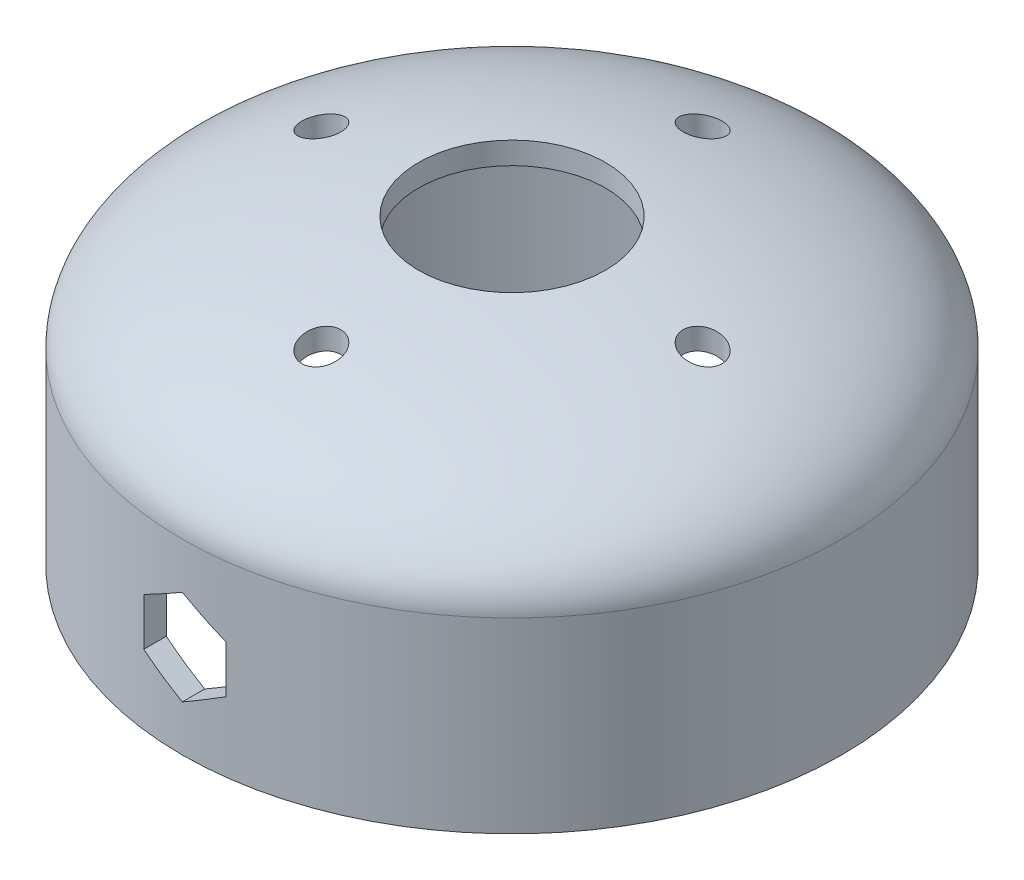
SolidWorks part; units mm, degrees
ref_plane "Front Plane" through (0, 0, 0) normal (0, 0, 1) x (1, 0, 0)
ref_plane "Top Plane" through (0, 0, 0) normal (0, 1, 0) x (1, 0, 0)
ref_plane "Right Plane" through (0, 0, 0) normal (1, 0, 0) x (0, 0, -1)
sketch "Sketch1" plane through (0, 0, 0) normal (0, 0, 1) x (1, 0, 0)
  line L0 (0, 0) -> (41.1, 0) construction
  line L1 (41.1, 0) -> (41.1, 25)
  line L2 (0, 0) -> (0, 69.4201) construction
  line L3 (41.1, 0) -> (44.1, 0)
  line L4 (44.1, 0) -> (44.1, 25)
  line L5 (41.1, 25) -> (0, 25) construction
  line L6 (0, 38) -> (0, 41)
  ellipse E0 centre (0, 25) end of major axis (44.1, 25) minor radius 16 (0, 41) -> (44.1, 25) cw
  ellipse E1 centre (0, 25) end of major axis (41.1, 25) minor radius 13 (0, 38) -> (41.1, 25) cw
  point P3 (44.1, 12.5)
  dimension "D1" = 41.1
  dimension "D2" = 3
  dimension "D3" = 25
  dimension "D4" = 25
  dimension "D5" = 16
  dimension "D6" = 3
revolve "Revolve1" add sketch "Sketch1" angle 360 about L6
sketch "Sketch2" plane through (0, 0, 0) normal (0, 1, 0) x (1, 0, 0)
  line L0 (0, -25.5) -> (0, 25.5) construction
  line L1 (25.5, 0) -> (-25.5, 0) construction
  circle A0 centre (0, 0) radius 25.5 construction
  circle A1 centre (25.5, 0) radius 2.6
  circle A2 centre (0, -25.5) radius 2.6
  circle A3 centre (-25.5, 0) radius 2.6
  circle A4 centre (0, 25.5) radius 2.6
  circle A5 centre (0, 0) radius 12.5
  point P17 (0, 0)
  dimension "D1" = 51
  dimension "D2" = 5.2
  dimension "D4" = 25
  dimension "D3" = 4
extrude "Cut-Extrude2" cut sketch "Sketch2" along normal through all
sketch "Sketch3" plane through (0, 0, 0) normal (0, 0, 1) x (1, 0, 0)
  line L0 (0, 0) -> (0, 25) construction
  line L1 (44.1, 25) -> (-44.1, 25) construction
  line L3 (0, 18.8509) -> (-5.5, 15.6754)
  line L4 (-5.5, 15.6754) -> (-5.5, 9.3246)
  line L5 (-5.5, 9.3246) -> (0, 6.1491)
  line L6 (0, 6.1491) -> (5.5, 9.3246)
  line L7 (5.5, 9.3246) -> (5.5, 15.6754)
  line L8 (5.5, 15.6754) -> (0, 18.8509)
  circle A0 centre (0, 12.5) radius 5.5 construction
  dimension "D1" = 11
extrude "Cut-Extrude4" cut sketch "Sketch3" against normal through all both and the other way through all
